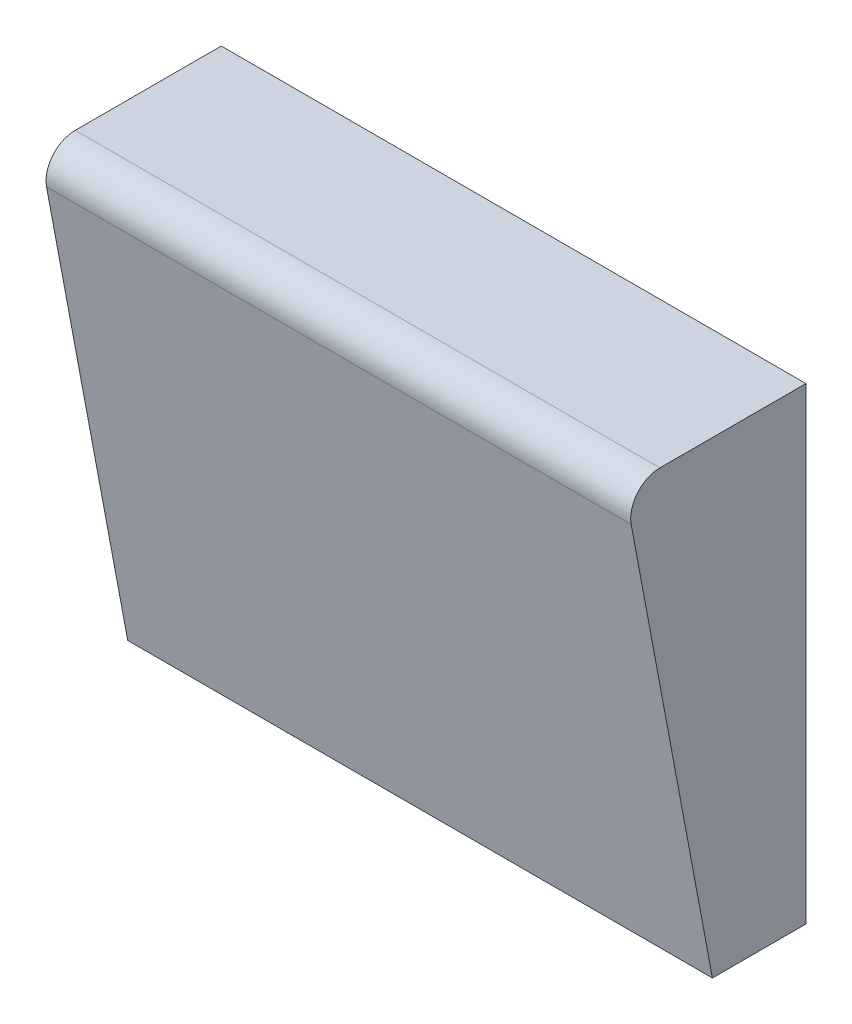
SolidWorks part; units mm, degrees
ref_plane "前视基准面" through (0, 0, 0) normal (0, 0, 1) x (1, 0, 0)
ref_plane "上视基准面" through (0, 0, 0) normal (0, 1, 0) x (1, 0, 0)
ref_plane "右视基准面" through (0, 0, 0) normal (1, 0, 0) x (0, 0, -1)
other "Configuration Table"
sketch "草图1" plane through (0, 0, 0) normal (1, 0, 0) x (0, 0, -1)
  line L0 (0, 0) -> (0.2, 0)
  line L1 (0.2, 0) -> (0.2, 32.02)
  line L2 (0.2, 32.02) -> (-6, 32.02)
  line L3 (-6, 32.02) -> (0, 0)
  dimension "D1" = 0.2
  dimension "D2" = 32.02
  dimension "D3" = 6.2
extrude "凸台-拉伸1" add sketch "草图1" along normal blind 20
sketch "草图3" plane through (0, 0, -0.2) normal (0, 0, -1) x (-1, 0, 0)
  line L0 (-10, 32.02) -> (-10, 25) construction
  line L1 (-20, 32.02) -> (0, 32.02) construction
  line L2 (-10, 0) -> (-10, 5) construction
  line L3 (-20, 0) -> (0, 0) construction
  circle A0 centre (-10, 25) radius 2.25
  circle A1 centre (-10, 5) radius 2.25
  dimension "D3" = 4.5
  dimension "D4" = 4.5
  dimension "D1" = 20
  dimension "D2" = 5
extrude "切除-拉伸1" cut sketch "草图3" against normal blind 2.5
fillet "圆角1" radius 1 2 edges at (10, 0, 0) (10, 32.02, 6)
sketch "草图4" plane through (20, 0, 0) normal (1, 0, 0) x (0, 0, -1)
  line L0 (0.2, 16.01) -> (-6.4564, 16.01) construction
  line L1 (0.2, 0) -> (0.2, 32.02) construction
  line L3 (-6.4564, 16.01) -> (3.7033, 16.01)
  line L4 (-6.4564, 16.01) -> (-6.4564, 0)
  line L5 (-6.4564, 0) -> (3.7033, 0)
  line L6 (3.7033, 16.01) -> (3.7033, 0)
extrude "切除-拉伸2" cut sketch "草图4" against normal blind 30
sketch "草图5" plane through (0, 0, 2.3) normal (0, 0, -1) x (-1, 0, 0)
  circle A0 centre (-10, 25) radius 1.5
  dimension "D1" = 3
extrude "切除-拉伸3" cut sketch "草图5" against normal blind 2
